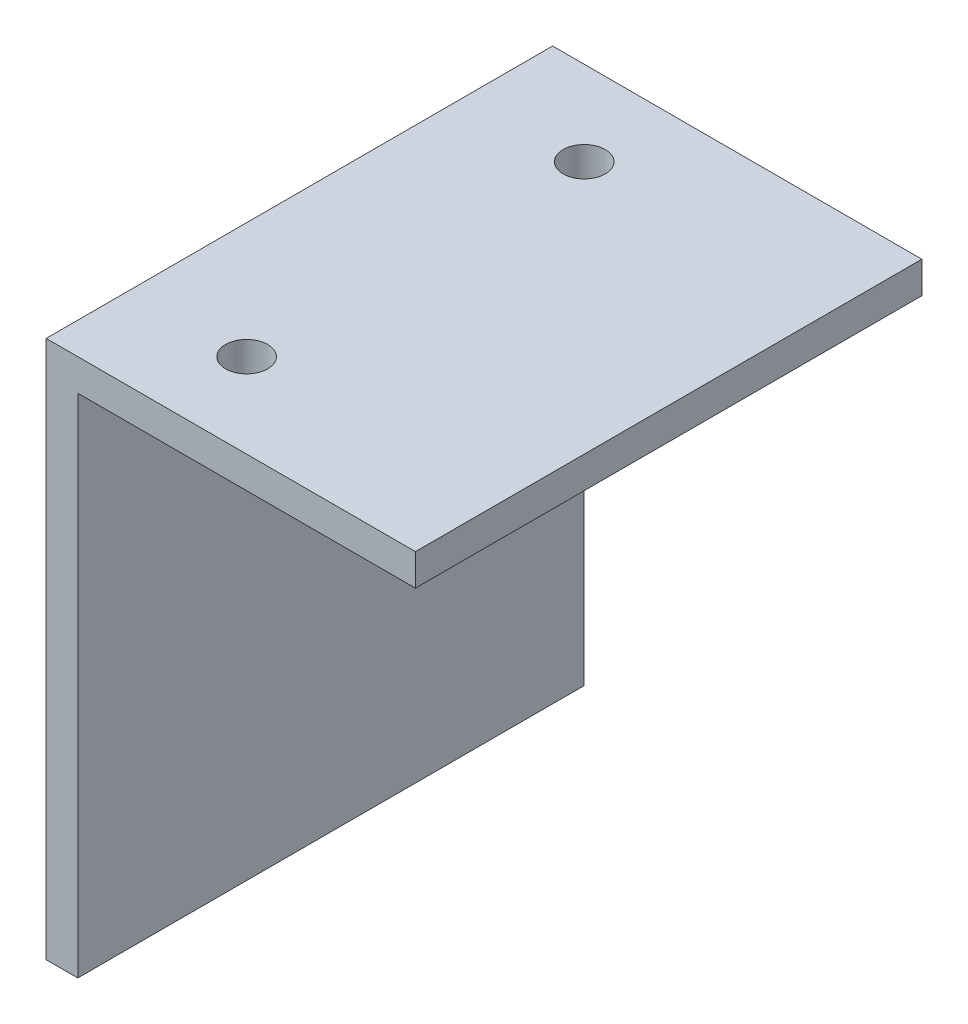
SolidWorks part; units mm, degrees
ref_plane "Front Plane" through (0, 0, 0) normal (0, 0, 1) x (1, 0, 0)
ref_plane "Top Plane" through (0, 0, 0) normal (0, 1, 0) x (1, 0, 0)
ref_plane "Right Plane" through (0, 0, 0) normal (1, 0, 0) x (0, 0, -1)
sketch "Sketch1" plane through (0, 0, 0) normal (0, 1, 0) x (1, 0, 0)
  line L0 (0, 0) -> (-50.4776, 0) construction
  line L1 (17.5, -24) -> (-17.5, -24)
  line L2 (17.5, -24) -> (17.5, 24)
  line L3 (17.5, 24) -> (-17.5, 24)
  line L4 (-17.5, -24) -> (-17.5, 24)
  line L5 (17.5, -24) -> (-17.5, 24) construction
  line L6 (17.5, 24) -> (-17.5, -24) construction
  circle A0 centre (-6.5, 16) radius 2
  circle A1 centre (-6.5, -16) radius 2
  point P0 (0, 0)
  dimension "D3" = 4
  dimension "D1" = 35
  dimension "D2" = 48
  dimension "D4" = 11
  dimension "D5" = 8
extrude "Boss-Extrude1" add sketch "Sketch1" along normal blind 3
sketch "Sketch2" plane through (0, 0, 0) normal (0, -1, 0) x (1, 0, 0)
  line L0 (-17.5, 24) -> (-17.5, -24)
  line L1 (-17.5, 24) -> (-14.5, 24)
  line L2 (-17.5, -24) -> (-14.5, -24)
  line L3 (-14.5, 24) -> (-14.5, -24)
  dimension "D1" = 3
extrude "Boss-Extrude2" add sketch "Sketch2" along normal blind 48
